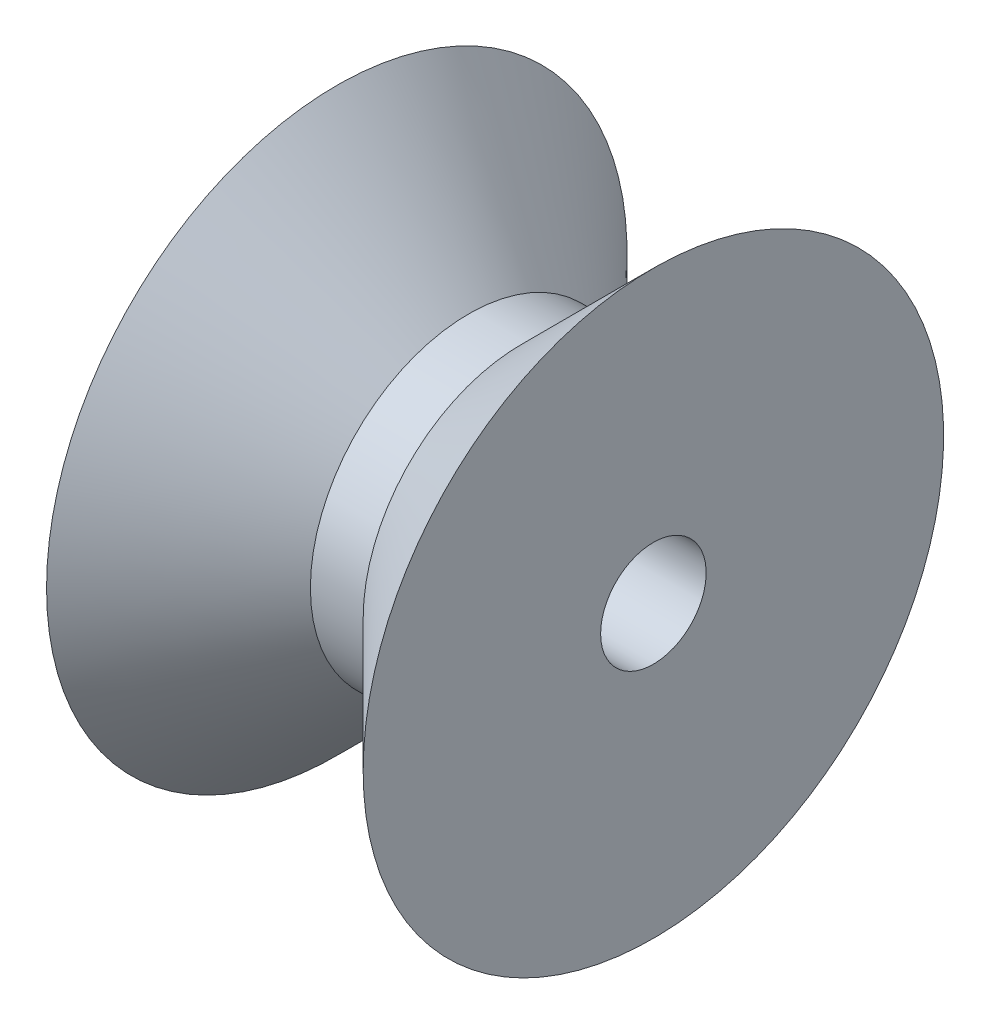
SolidWorks part; units mm, degrees
ref_plane "Front Plane" through (0, 0, 0) normal (0, 0, 1) x (1, 0, 0)
ref_plane "Top Plane" through (0, 0, 0) normal (0, 1, 0) x (1, 0, 0)
ref_plane "Right Plane" through (0, 0, 0) normal (1, 0, 0) x (0, 0, -1)
sketch "Sketch1" plane through (0, 0, 0) normal (0, 1, 0) x (1, 0, 0)
  line L0 (-30.1775, 0) -> (29.6163, 0) construction
  line L1 (0, 22.7266) -> (0, -18.6115) construction
  line L2 (6, 0) -> (-6, 0)
  line L3 (-6, 0) -> (-6, 11)
  line L4 (-6, 11) -> (-1, 6)
  line L5 (-1, 6) -> (1, 6)
  line L6 (6, 11) -> (1, 6)
  line L7 (6, 0) -> (6, 11)
  point P12 (0, 6)
  point P13 (0, 0)
  dimension "D1" = 11
  dimension "D2" = 6
  dimension "D3" = 45
  dimension "D4" = 6
revolve "Revolve2" add sketch "Sketch1" angle 360 about L0
sketch "Sketch2" plane through (-6, 0, 0) normal (-1, 0, 0) x (0, 0, 1)
  circle A0 centre (0, 0) radius 2
  dimension "D1" = 4
extrude "Cut-Extrude2" cut sketch "Sketch2" against normal blind 12
